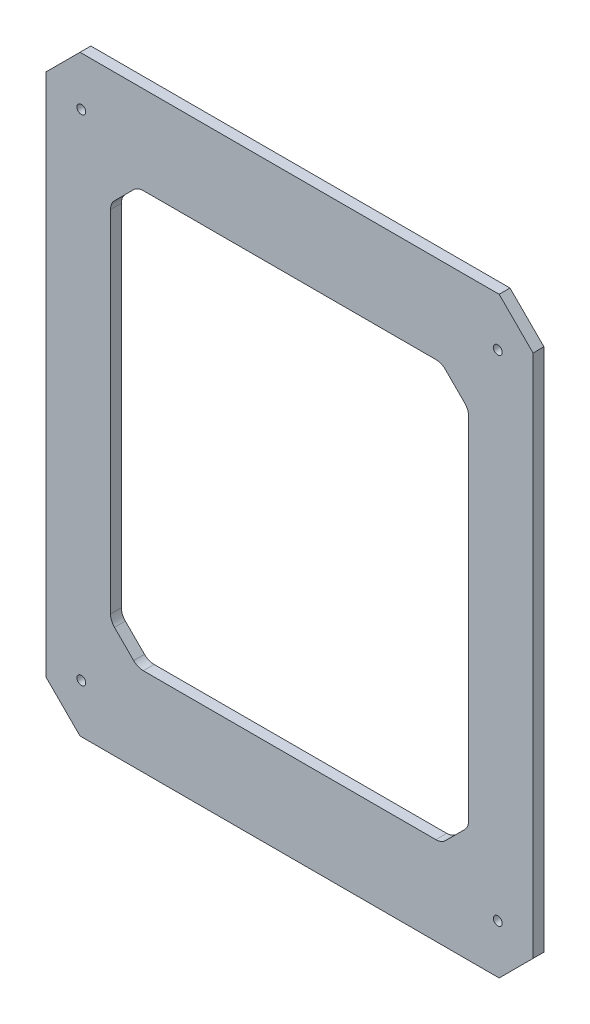
SolidWorks part; units mm, degrees
ref_plane "Front" through (0, 0, 0) normal (0, 0, 1) x (1, 0, 0)
ref_plane "Top" through (0, 0, 0) normal (0, 1, 0) x (1, 0, 0)
ref_plane "Right" through (0, 0, 0) normal (1, 0, 0) x (0, 0, -1)
ref_plane "Plane1" through (0, 0, 8) normal (0, 0, 1) x (1, 0, 0)
sketch "Sketch1" plane through (0, 0, 8) normal (0, 0, 1) x (1, 0, 0)
  line L0 (-154.5, -218.25) -> (154.5, -218.25)
  line L1 (154.5, -218.25) -> (179.5, -193.25)
  line L2 (179.5, -193.25) -> (179.5, 193.25)
  line L3 (179.5, 193.25) -> (154.5, 218.25)
  line L4 (154.5, 218.25) -> (-154.5, 218.25)
  line L5 (-154.5, 218.25) -> (-179.5, 193.25)
  line L6 (-179.5, 193.25) -> (-179.5, -193.25)
  line L7 (-179.5, -193.25) -> (-154.5, -218.25)
extrude "Boss-Extrude1" add sketch "Sketch1" against normal blind 8
sketch "Sketch2" plane through (0, 0, 0) normal (0, 0, -1) x (-1, 0, 0)
  line L0 (-107.8579, -153.25) -> (107.8579, -153.25)
  line L1 (114.9289, -150.3211) -> (129.0711, -136.1789)
  line L2 (132, -129.1079) -> (132, 129.1079)
  line L3 (129.0711, 136.1789) -> (114.9289, 150.3211)
  line L4 (107.8579, 153.25) -> (-107.8579, 153.25)
  line L5 (-114.9289, 150.3211) -> (-129.0711, 136.1789)
  line L6 (-132, 129.1079) -> (-132, -129.1079)
  line L7 (-129.0711, -136.1789) -> (-114.9289, -150.3211)
  arc A0 (107.8579, -153.25) -> (114.9289, -150.3211) centre (107.8579, -143.25) ccw
  arc A1 (129.0711, -136.1789) -> (132, -129.1079) centre (122, -129.1079) ccw
  arc A2 (132, 129.1079) -> (129.0711, 136.1789) centre (122, 129.1079) ccw
  arc A3 (114.9289, 150.3211) -> (107.8579, 153.25) centre (107.8579, 143.25) ccw
  arc A4 (-107.8579, 153.25) -> (-114.9289, 150.3211) centre (-107.8579, 143.25) ccw
  arc A5 (-129.0711, 136.1789) -> (-132, 129.1079) centre (-122, 129.1079) ccw
  arc A6 (-132, -129.1079) -> (-129.0711, -136.1789) centre (-122, -129.1079) ccw
  arc A7 (-114.9289, -150.3211) -> (-107.8579, -153.25) centre (-107.8579, -143.25) ccw
extrude "Cut-Extrude1" cut sketch "Sketch2" against normal through all
hole_wizard "Ø6.5 (6.5) Diameter Hole2" positions "Sketch6" profile "Sketch5" hole size "Ø6.5" standard "ANSI Metric"
sketch "Sketch6" plane through (0, 0, 0) normal (0, 0, -1) x (-1, 0, 0)
  line L0 (0, 125.6826) -> (0, 0) construction
  line L1 (0, 0) -> (110.0113, 0) construction
  point P0 (-153.5, -182.25)
  point P1 (153.5, -182.25)
  point P2 (-153.5, 182.25)
  point P12 (153.5, 182.25)
  dimension "D1" = 364.5
  dimension "D2" = 307
sketch "Sketch5" plane through (153.5, -182.25, 0) normal (1, 0, 0) x (0, 1, 0)
  line L0 (0, 0) -> (0, 8)
  line L1 (0, 8) -> (3.25, 8)
  line L2 (3.25, 8) -> (3.25, 0)
  line L5 (3.25, 0) -> (0, 0)
  line L11 (0, -6.35) -> (0, 107.95) construction
  dimension "Thru Hole Dia." = 6.5
  dimension "Thru Hole Depth" = 8
